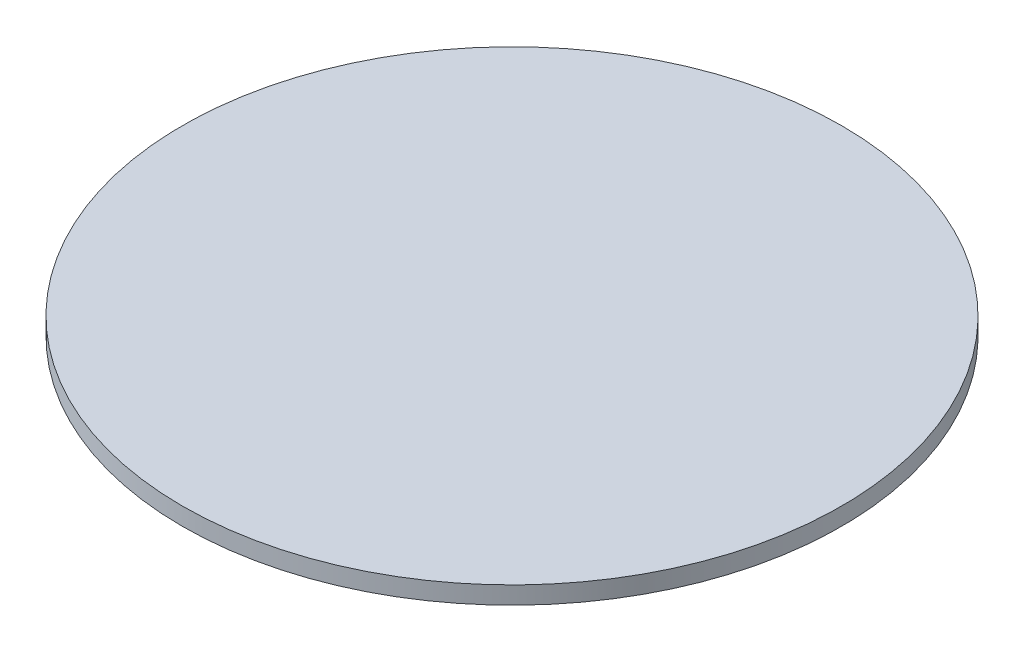
SolidWorks part; units mm, degrees
material "Glass"
ref_plane "Front Plane" through (0, 0, 0) normal (0, 0, 1) x (1, 0, 0)
ref_plane "Top Plane" through (0, 0, 0) normal (0, 1, 0) x (1, 0, 0)
ref_plane "Right Plane" through (0, 0, 0) normal (1, 0, 0) x (0, 0, -1)
sketch "Sketch4" plane through (0, 0, 0) normal (0, 1, 0) x (1, 0, 0)
  circle A0 centre (0, 0) radius 75
sketch "Sketch5" plane through (0, 0, 0) normal (0, 1, 0) x (1, 0, 0)
  circle A0 centre (0, 0) radius 75
extrude "Boss-Extrude2" add sketch "Sketch5" along normal blind 4
